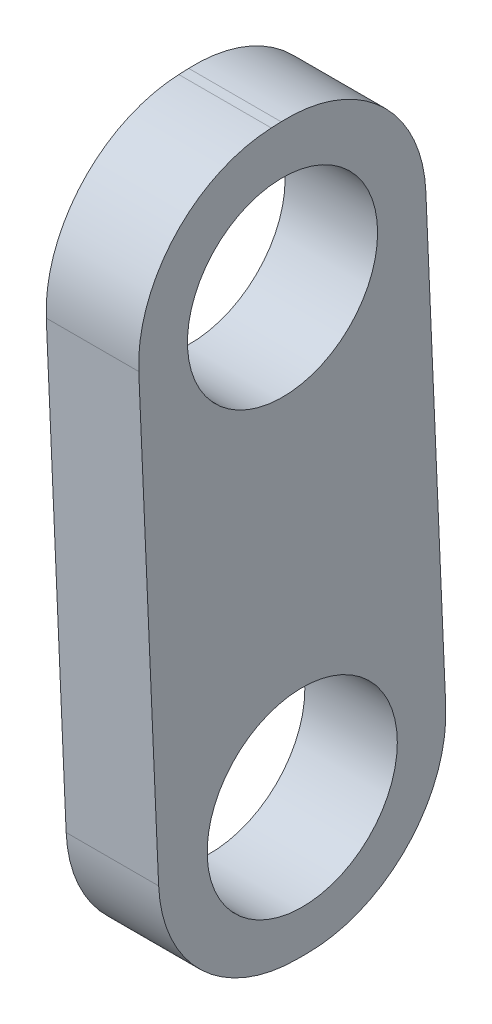
SolidWorks part; units mm, degrees
material "ABS"
ref_plane "Front Plane" through (0, 0, 0) normal (0, 0, 1) x (1, 0, 0)
ref_plane "Top Plane" through (0, 0, 0) normal (0, 1, 0) x (1, 0, 0)
ref_plane "Right Plane" through (0, 0, 0) normal (1, 0, 0) x (0, 0, -1)
sketch "Sketch1" plane through (0, 0, 0) normal (1, 0, 0) x (0, 0, -1)
  line L0 (0, 0) -> (177.8, 0) construction
  line L1 (0, 0) -> (177.1234, 15.4963) construction
  line L2 (183.1817, 7.9979) -> (182.8874, 14.7383) construction
  line L3 (182.8874, 14.7383) -> (190.8174, 15.0846) construction
  line L4 (0, 0) -> (187.1467, 8.171) construction
  line L5 (190.8174, 15.0846) -> (191.406, 1.6037) construction
  line L6 (191.406, 1.6037) -> (183.476, 1.2574) construction
  line L7 (183.476, 1.2574) -> (183.1817, 7.9979) construction
  line L8 (182.8874, 14.7383) -> (191.406, 1.6037) construction
  line L9 (191.406, 1.6037) -> (190.8174, 15.0846) construction
  line L10 (190.8174, 15.0846) -> (183.476, 1.2574) construction
  line L11 (183.1817, 7.9979) -> (180.0098, 7.8594) construction
  line L12 (180.0098, 7.8594) -> (179.8674, 11.1202) construction
  line L13 (179.8674, 11.1202) -> (183.0394, 11.2587) construction
  line L14 (180.0098, 7.8594) -> (180.1521, 4.5986) construction
  line L15 (180.1521, 4.5986) -> (183.3241, 4.7371) construction
  line L16 (177.1234, 15.4963) -> (177.8, 0) construction
  line L17 (182.3887, 7.9633) -> (181.8348, 20.6512)
  line L18 (181.8348, 20.6512) -> (171.9807, 20.2209)
  line L19 (182.3887, 7.9633) -> (182.9427, -4.7246)
  line L20 (182.9427, -4.7246) -> (173.0699, -4.7246)
  line L21 (173.0699, -4.7246) -> (171.9807, 20.2209)
  line L22 (177.1234, 15.4963) -> (176.9077, 20.4361) construction
  line L23 (177.8, 0) -> (178.0063, -4.7246) construction
  circle A0 centre (177.1234, 15.4963) radius 3.2639
  circle A1 centre (177.8, 0) radius 3.2639
  point P23 (181.4534, 11.1894)
  point P24 (176.9077, 20.4361)
  point P25 (0, 0)
  dimension "D4" = 6.5278
  dimension "D5" = 6.5278
  dimension "D1" = 177.8
  dimension "D2" = 5
  dimension "D3" = 177.8
  dimension "D6" = 187.325
  dimension "D7" = 7.9375
  dimension "D8" = 13.4937
  dimension "D9" = 3.175
  dimension "D10" = 6.5278
  dimension "D11" = 2.5
  dimension "D12" = 12.7
  dimension "D14" = 12.7
  dimension "D16" = 0.7937
extrude "Boss-Extrude1" add sketch "Sketch1" along normal blind 3.175
fillet "Fillet2" radius 4.7625 4 edges at (1.5875, 20.6512, -181.8348) (1.5875, -4.7246, -182.9427) (1.5875, -4.7246, -173.0699) (1.5875, 20.2209, -171.9807)
sketch "Sketch3" plane through (0, 7.9633, -182.3887) normal (0, 0.0436, -0.999) x (-1, 0, 0)
  line L0 (0, 0.1062) -> (0.7937, 0.1062) construction
  line L1 (0, -7.725) -> (0, 7.9375) construction
  circle A0 centre (0.7937, 0.1062) radius 3.2639
  dimension "D2" = 6.5278
  dimension "D1" = 0.7937
extrude "Cut-Extrude1" cut sketch "Sketch3" against normal blind 3.175
